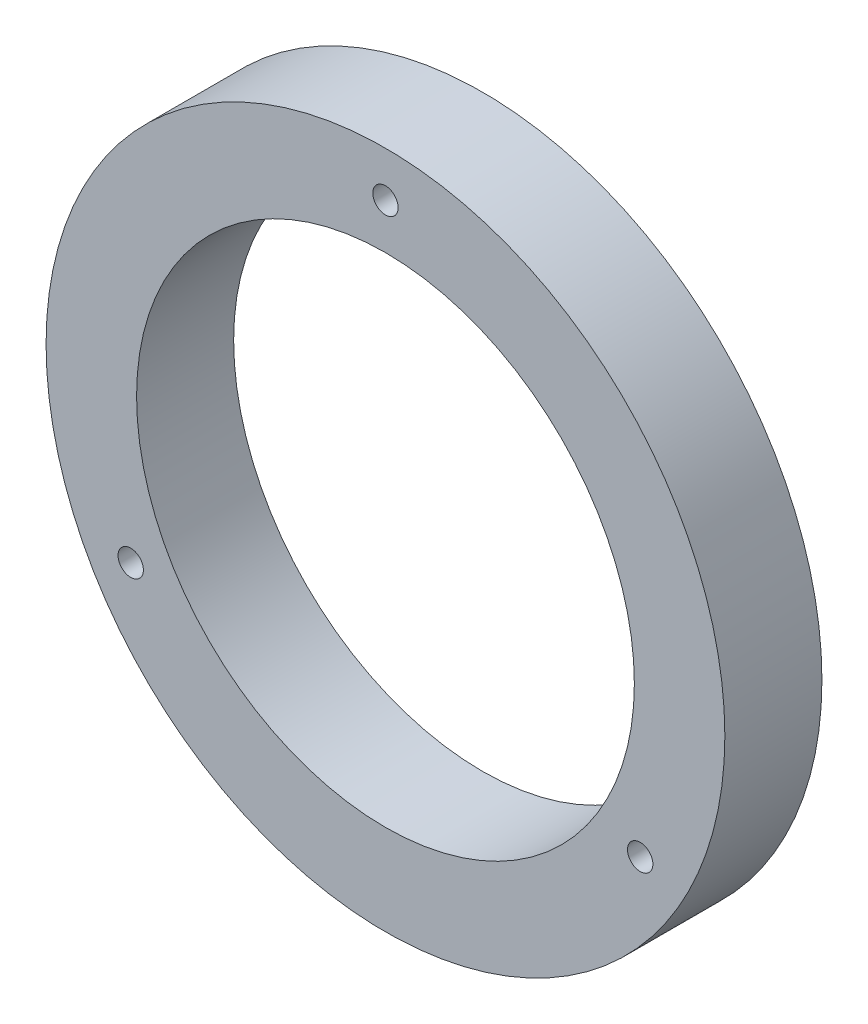
SolidWorks part; units mm, degrees
ref_plane "Front Plane" through (0, 0, 0) normal (0, 0, 1) x (1, 0, 0)
ref_plane "Top Plane" through (0, 0, 0) normal (0, 1, 0) x (1, 0, 0)
ref_plane "Right Plane" through (0, 0, 0) normal (1, 0, 0) x (0, 0, -1)
sketch "Sketch1" plane through (0, 0, 0) normal (0, 0, 1) x (1, 0, 0)
  circle A0 centre (0, 0) radius 75
  circle A1 centre (0, 0) radius 55
extrude "Boss-Extrude1" add sketch "Sketch1" along normal blind 21.45 contours A0 | A1
sketch "Sketch3" plane through (0, 0, 0) normal (0, 0, -1) x (-1, 0, 0)
  circle A0 centre (0, 65) radius 2.8
  circle A1 centre (56.2917, -32.5) radius 2.8
  circle A2 centre (-56.2917, -32.5) radius 2.8
  point P9 (0, 0)
  dimension "D1" = 3
extrude "Cut-Extrude1" cut sketch "Sketch3" against normal blind 27.8
